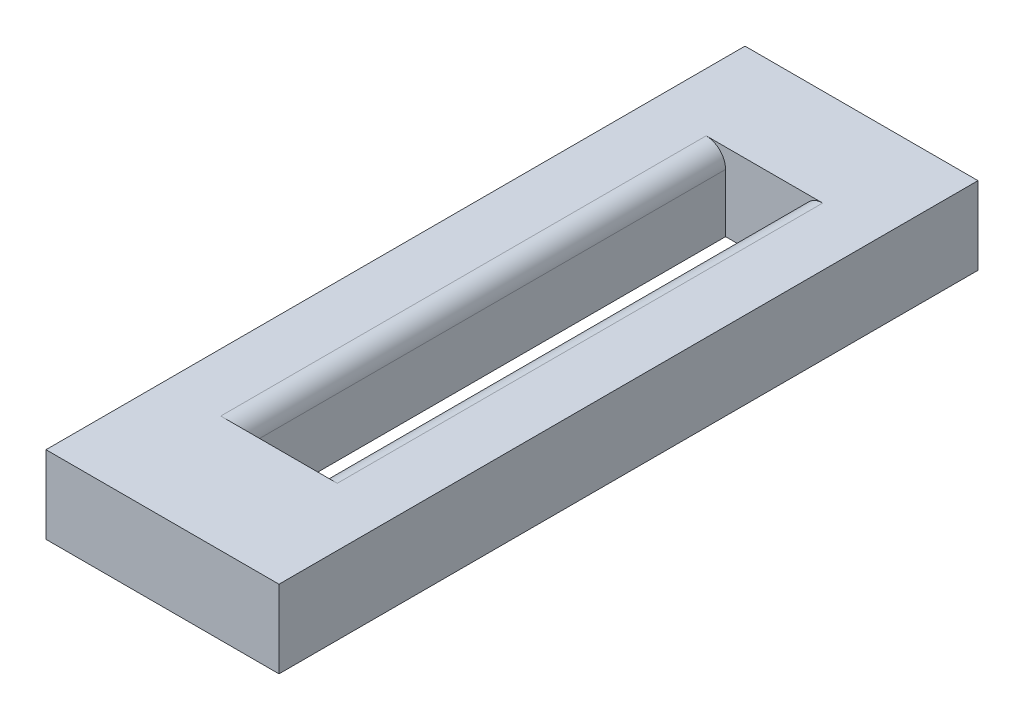
SolidWorks part; units mm, degrees
ref_plane "前基準面" through (0, 0, 0) normal (0, 0, 1) x (1, 0, 0)
ref_plane "上基準面" through (0, 0, 0) normal (0, 1, 0) x (1, 0, 0)
ref_plane "右基準面" through (0, 0, 0) normal (1, 0, 0) x (0, 0, -1)
sketch "草圖2" plane through (0, 0, 0) normal (0, 0, 1) x (1, 0, 0)
  line L0 (-30, 10) -> (30, 10)
  line L2 (-30, 10) -> (-30, -10)
  line L3 (-30, -10) -> (30, -10)
  line L4 (30, 10) -> (30, -10)
  line L5 (-30, 10) -> (30, -10) construction
  line L6 (30, 10) -> (-30, -10) construction
  point P0 (0, 0)
  dimension "D3" = 60
  dimension "D2" = 20
extrude "填料-伸長1" add sketch "草圖2" against normal blind 180
ref_plane "平面1" through (0, 0, -30) normal (0, 0, 1) x (1, 0, 0)
sketch "草圖13" plane through (0, 10, 0) normal (0, 1, 0) x (1, 0, 0)
  line L0 (0, -8.5668) -> (0, 154.432) construction
  line L1 (-60, 30) -> (60, 30) construction
  line L2 (30, 0) -> (-30, 0) construction
  line L3 (30, 180) -> (-30, 180) construction
  line L4 (-90, 0) -> (90, 0)
  line L5 (-90, 0) -> (-90, 180)
  line L6 (-90, 180) -> (90, 180)
  line L7 (90, 0) -> (90, 180)
  circle A0 centre (0, 97.3796) radius 35 construction
  circle A1 centre (-60, 30) radius 32.5 construction
  circle A2 centre (60, 30) radius 32.5 construction
  circle A3 centre (-60, 30) radius 25 construction
  circle A4 centre (60, 30) radius 25 construction
  point P3 (0, 180)
  point P14 (60, 30)
  point P22 (-60, 30)
  dimension "D2" = 70
  dimension "D3" = 65
  dimension "D7" = 50
  dimension "D1" = 30
  dimension "D4" = 60
  dimension "D5" = 180
sketch "草圖14" plane through (0, 10, 0) normal (0, 1, 0) x (1, 0, 0)
  line L0 (0, 154.2144) -> (0, -6.173) construction
  line L2 (-10, 155) -> (10, 155)
  line L3 (-10, 155) -> (-10, 30)
  line L4 (-10, 30) -> (10, 30)
  line L5 (10, 155) -> (10, 30)
  line L6 (-10, 155) -> (10, 30) construction
  line L7 (-10, 30) -> (10, 155) construction
  line L9 (30, 0) -> (-30, 0) construction
  line L11 (10, 115) -> (-10, 115) construction
  line L12 (10, 115) -> (10, 35) construction
  line L13 (10, 35) -> (-10, 35) construction
  line L14 (-10, 115) -> (-10, 35) construction
  point P3 (0, 92.5)
  point P11 (-10, 75)
  point P13 (0, 115)
  point P16 (0, 75)
  dimension "D1" = 20
  dimension "D2" = 125
  dimension "D3" = 30
  dimension "D4" = 80
  dimension "D5" = 20
  dimension "D6" = 40
extrude "除料-伸長1" cut sketch "草圖14" against normal through all
sketch "草圖15" plane through (0, 10, 0) normal (0, 1, 0) x (1, 0, 0)
  line L0 (0, -108.9241) -> (0, 108.9241) construction
  line L1 (-60, 55) -> (60, 55) construction
  line L4 (30, 0) -> (-30, 0) construction
  circle A0 centre (-60, 55) radius 25
  circle A1 centre (60, 55) radius 25
  circle A2 centre (-60, 55) radius 32.5 construction
  circle A3 centre (60, 55) radius 32.5 construction
  circle A4 centre (0, 55) radius 35 construction
  dimension "D1" = 65
  dimension "D3" = 50
  dimension "D4" = 70
  dimension "D2" = 60
  dimension "D5" = 55
fillet "圓角1" radius 5 2 edges at (-10, 10, -92.5) (10, 10, -92.5)
